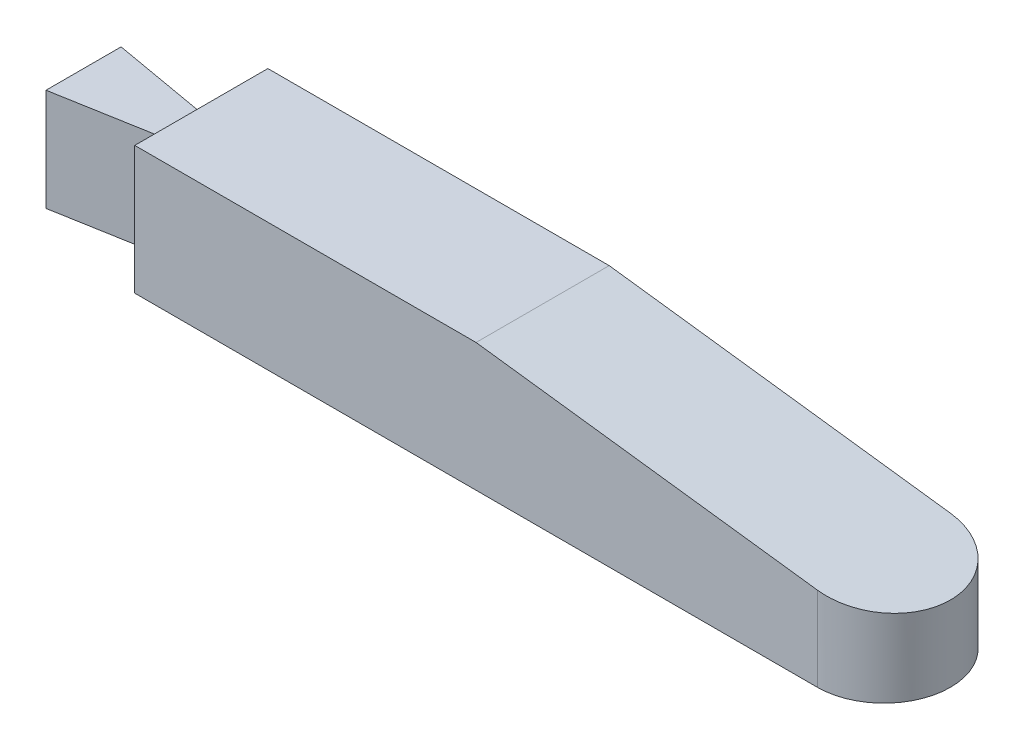
SolidWorks part; units mm, degrees
ref_plane "Front Plane" through (0, 0, 0) normal (0, 0, 1) x (1, 0, 0)
ref_plane "Top Plane" through (0, 0, 0) normal (0, 1, 0) x (1, 0, 0)
ref_plane "Right Plane" through (0, 0, 0) normal (1, 0, 0) x (0, 0, -1)
sketch "Sketch2" plane through (0, 0, 0) normal (0, 1, 0) x (1, 0, 0)
  line L10 (0, -14.8166) -> (0, -24.8074) construction
  line L29 (-35.052, -8.636) -> (-35.052, -30.988)
  line L30 (-35.052, -8.636) -> (0, -14.8166)
  line L31 (-35.052, -30.988) -> (0, -24.8074)
  line L32 (0, 0) -> (203.2, 0)
  line L33 (0, -39.624) -> (203.2, -39.624)
  line L35 (0, 0) -> (0, -14.8166)
  line L36 (0, -39.624) -> (0, -24.8074)
  line L37 (-35.052, -19.812) -> (0, -19.812) construction
  arc A5 (203.2, 0) -> (203.2, -39.624) centre (203.2, -19.812) cw
  point P9 (0, 0)
  point P10 (0, 0)
  point P13 (0, 0)
  point P14 (0, 0)
  dimension "D4" = 14.8166
  dimension "D5" = 39.624
  dimension "D3" = 22.352
  dimension "D7" = 14.8166
  dimension "D1" = 35.052
  dimension "D2" = 80
  dimension "D6" = 203.2
extrude "Boss-Extrude1" add sketch "Sketch2" along normal blind 38.1
sketch "Sketch3" plane through (0, 38.1, 0) normal (0, 1, 0) x (1, 0, 0)
  line L0 (-35.052, -8.636) -> (-35.052, -30.988)
  line L1 (-35.052, -30.988) -> (0, -24.8074)
  line L2 (0, -24.8074) -> (0, -14.8166)
  line L3 (0, -14.8166) -> (-35.052, -8.636)
extrude "Cut-Extrude1" cut sketch "Sketch3" against normal blind 7.62
sketch "Sketch5" plane through (0, 0, 39.624) normal (0, 0, 1) x (1, 0, 0)
  line L5 (101.6, 38.1) -> (223.012, 22.5197)
  line L6 (0, 38.1) -> (203.2, 38.1) construction
  line L7 (223.012, 0) -> (223.012, 38.1) construction
  line L8 (223.012, 22.5197) -> (223.012, 38.1)
  line L9 (223.012, 38.1) -> (101.6, 38.1)
  dimension "D1" = 7.313
extrude "Cut-Extrude4" cut sketch "Sketch5" against normal blind 39.624
